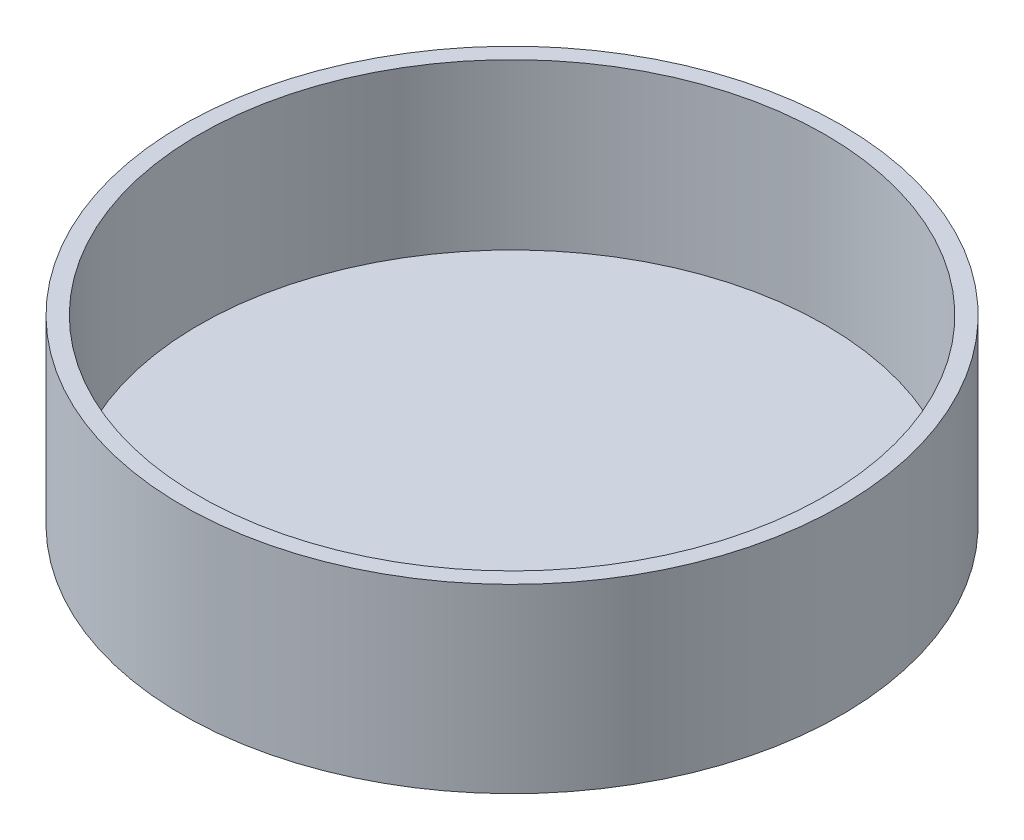
SolidWorks part; units mm, degrees
ref_plane "Front Plane" through (0, 0, 0) normal (0, 0, 1) x (1, 0, 0)
ref_plane "Top Plane" through (0, 0, 0) normal (0, 1, 0) x (1, 0, 0)
ref_plane "Right Plane" through (0, 0, 0) normal (1, 0, 0) x (0, 0, -1)
sketch "Sketch1" plane through (0, 0, 0) normal (0, 0, 1) x (1, 0, 0)
  line L0 (0, 0) -> (95, 0)
  line L1 (95, 0) -> (95, 50)
  line L2 (0, 0) -> (0, 50) construction
  dimension "D1" = 95
  dimension "D2" = 50
revolve "Revolve-Thin1" add sketch "Sketch1" angle 360 about L2
